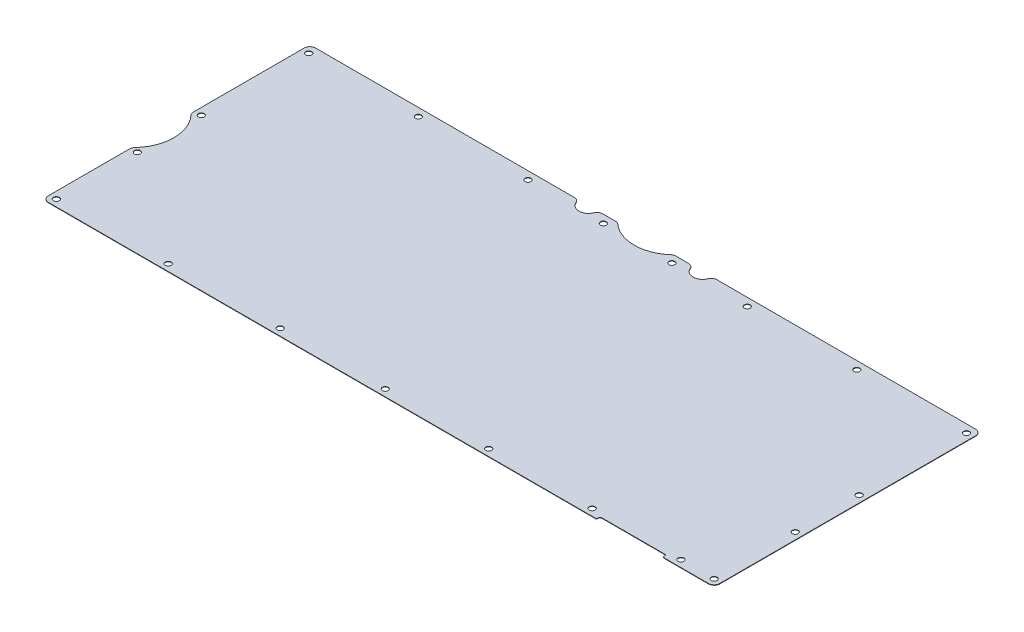
SolidWorks part; units mm, degrees
material "PE High Density Film"
ref_plane "Front Plane" through (0, 0, 0) normal (0, 0, 1) x (1, 0, 0)
ref_plane "Top Plane" through (0, 0, 0) normal (0, 1, 0) x (1, 0, 0)
ref_plane "Right Plane" through (0, 0, 0) normal (1, 0, 0) x (0, 0, -1)
sketch "Sketch1" plane through (0, 0, 0) normal (0, 1, 0) x (1, 0, 0)
  line L1 (-186.69, -74.6125) -> (186.69, -74.6125)
  line L2 (-186.69, -74.6125) -> (-186.69, 74.6125)
  line L3 (-186.69, 74.6125) -> (186.69, 74.6125)
  line L4 (186.69, -74.6125) -> (186.69, 74.6125)
  line L5 (-186.69, -74.6125) -> (186.69, 74.6125) construction
  line L6 (-186.69, 74.6125) -> (186.69, -74.6125) construction
  point P0 (0, 0)
  dimension "D1" = 149.225
  dimension "D2" = 373.38
extrude "Boss-Extrude1" add sketch "Sketch1" along normal blind 0.254
hole_wizard "#4 Clearance Hole2" positions "Sketch6" profile "Sketch5" hole size "#4" standard "Ansi Inch"
sketch "Sketch6" plane through (0, 0.254, 0) normal (0, 1, 0) x (-1, 0, 0)
  line L0 (-186.69, -74.6125) -> (186.69, -74.6125) construction
  line L1 (186.69, -74.6125) -> (186.69, 74.6125) construction
  point P0 (121.92, -70.1675)
  point P15 (60.96, -70.1675)
  point P16 (0, -70.1675)
  point P17 (-60.96, -70.1675)
  point P18 (-121.92, -70.1675)
  dimension "D1" = 4.445
  dimension "D2" = 64.77
  dimension "D4" = 60.96
  dimension "D3" = 5
sketch "Sketch5" plane through (-121.92, 0.254, -70.1675) normal (1, 0, 0) x (0, 0, 1)
  line L0 (0, 0) -> (0, 1.7426)
  line L1 (0, 1.7426) -> (1.6319, 0.762)
  line L2 (1.6319, 0.762) -> (1.6319, 0)
  line L5 (1.6319, 0) -> (0, 0)
  line L10 (0, 1.7426) -> (-1.6319, 0.762) construction
  line L11 (0, -6.35) -> (0, 107.95) construction
  dimension "Hole Dia." = 3.2639
  dimension "Hole Depth" = 0.762
  dimension "Drill Angle" = 118
sketch "Sketch7" plane through (0, 0.254, 0) normal (0, 1, 0) x (1, 0, 0)
  line L0 (186.69, 74.6125) -> (-186.69, 74.6125) construction
  circle A0 centre (0, 90.4875) radius 22.225
  dimension "D2" = 44.45
  dimension "D1" = 15.875
extrude "Cut-Extrude2" cut sketch "Sketch7" against normal up to next
fillet "Fillet2" radius 3.175 2 edges at (15.5543, 0.127, -74.6125) (-15.5543, 0.127, -74.6125)
hole_wizard "#4 Clearance Hole3" positions "Sketch9" profile "Sketch8" hole size "#4" standard "Ansi Inch" end condition up to next
sketch "Sketch9" plane through (0, 0.254, 0) normal (0, 1, 0) x (-1, 0, 0)
  line L0 (-186.69, -74.6125) -> (-16.8005, -74.6125) construction
  point P0 (19.05, -70.1675)
  point P1 (-19.05, -70.1675)
  dimension "D1" = 4.445
  dimension "D2" = 19.05
  dimension "D3" = 38.1
sketch "Sketch8" plane through (-19.05, 0.254, -70.1675) normal (1, 0, 0) x (0, 0, 1)
  line L0 (0, 0) -> (0, 0.254)
  line L1 (0, 0.254) -> (1.632, 0.254)
  line L2 (1.632, 0.254) -> (1.6319, 0)
  line L5 (1.6319, 0) -> (0, 0)
  line L11 (0, -6.35) -> (0, 107.95) construction
  dimension "Thru Hole Dia." = 3.2639
  dimension "Thru Hole Depth" = 0.254
sketch "Sketch10" plane through (0, 0.254, 0) normal (0, 1, 0) x (1, 0, 0)
  line L0 (186.69, 74.6125) -> (16.8005, 74.6125) construction
  circle A0 centre (31.75, 74.6125) radius 5.334
  circle A1 centre (-31.75, 74.6125) radius 5.334
  dimension "D1" = 10.668
  dimension "D2" = 63.5
  dimension "D3" = 31.75
extrude "Cut-Extrude3" cut sketch "Sketch10" against normal blind 1.016
fillet "Fillet3" radius 3.175 4 edges at (-37.084, 0.127, -74.6125) (-26.416, 0.127, -74.6125) (26.416, 0.127, -74.6125) (37.084, 0.127, -74.6125)
sketch "Sketch11" plane through (0, 0.254, 0) normal (0, 1, 0) x (1, 0, 0)
  line L0 (-186.69, 74.6125) -> (-186.69, -74.6125) construction
  line L1 (-39.6445, 74.6125) -> (-186.69, 74.6125) construction
  circle A0 centre (-202.565, -7.9375) radius 22.86
  dimension "D2" = 45.72
  dimension "D1" = 15.875
  dimension "D3" = 82.55
extrude "Cut-Extrude4" cut sketch "Sketch11" against normal through all
fillet "Fillet4" radius 3.175 4 edges at (186.69, 0.127, -74.6125) (-186.69, 0.127, -74.6125) (-186.69, 0.127, 24.3863) (-186.69, 0.127, -8.5113)
hole_wizard "#4 Clearance Hole4" positions "Sketch13" profile "Sketch14" hole size "#4" standard "Ansi Inch" end condition up to next
sketch "Sketch13" plane through (0, 0.254, 0) normal (0, 1, 0) x (-1, 0, 0)
  line L0 (186.69, 74.6125) -> (-186.69, 74.6125) construction
  line L1 (186.69, 25.6834) -> (186.69, 74.6125) construction
  line L2 (39.6445, -74.6125) -> (183.515, -74.6125) construction
  point P1 (182.88, -70.1675)
  point P3 (182.88, -10.4775)
  point P5 (182.88, 25.0825)
  point P7 (182.88, 70.1675)
  dimension "D1" = 4.445
  dimension "D2" = 3.81
  dimension "D3" = 45.085
  dimension "D4" = 4.445
  dimension "D5" = 35.56
sketch "Sketch14" plane through (-182.88, 0.254, -70.1675) normal (1, 0, 0) x (0, 0, 1)
  line L0 (0, 0) -> (0, 0.255)
  line L1 (0, 0.255) -> (1.632, 0.255)
  line L2 (1.632, 0.255) -> (1.6319, 0)
  line L5 (1.6319, 0) -> (0, 0)
  line L11 (0, -6.35) -> (0, 107.95) construction
  dimension "Thru Hole Dia." = 3.2639
  dimension "Thru Hole Depth" = 0.255
mirror "Mirror1" about plane through (0, 0, 0) normal (1, 0, 0) of "#4 Clearance Hole4"
sketch "Sketch15" plane through (0, 0.254, 0) normal (0, 1, 0) x (1, 0, 0)
  line L0 (-186.69, -74.6125) -> (186.69, -74.6125) construction
  line L1 (158.0515, -74.6125) -> (121.3485, -74.6125)
  line L2 (158.0515, -74.6125) -> (158.0515, -72.009)
  line L3 (158.0515, -72.009) -> (121.3485, -72.009)
  line L4 (121.3485, -74.6125) -> (121.3485, -72.009)
  line L5 (186.69, -74.6125) -> (186.69, 71.4375) construction
  dimension "D1" = 2.6035
  dimension "D2" = 36.703
  dimension "D3" = 28.6385
extrude "Cut-Extrude5" cut sketch "Sketch15" against normal through all
hole_wizard "#4 Clearance Hole5" positions "Sketch17" profile "Sketch18" hole size "#4" standard "Ansi Inch" end condition up to next
sketch "Sketch17" plane through (0, 0.254, 0) normal (0, 1, 0) x (-1, 0, 0)
  line L1 (-186.69, 74.6125) -> (-186.69, -71.4375) construction
  line L3 (-158.0515, 74.6125) -> (-186.69, 74.6125) construction
  circle A0 centre (182.88, 70.1675) radius 1.6319 construction
  point P0 (-115.062, 70.1675)
  point P1 (-164.465, 70.1675)
  point P9 (0, 70.1675)
  point P11 (-57.531, 70.1675)
  point P13 (120.65, 70.1675)
  point P15 (58.42, 70.1675)
  dimension "D5" = 62.23
  dimension "D1" = 4.445
  dimension "D2" = 49.403
  dimension "D3" = 22.225
  dimension "D4" = 57.531
  dimension "D6" = 62.23
sketch "Sketch18" plane through (115.062, 0.254, 70.1675) normal (1, 0, 0) x (0, 0, 1)
  line L0 (0, 0) -> (0, 0.254)
  line L1 (0, 0.254) -> (1.632, 0.254)
  line L2 (1.632, 0.254) -> (1.6319, 0)
  line L5 (1.6319, 0) -> (0, 0)
  line L11 (0, -6.35) -> (0, 107.95) construction
  dimension "Thru Hole Dia." = 3.2639
  dimension "Thru Hole Depth" = 0.254
sketch "Sketch20" plane through (0, 0.254, 0) normal (0, 1, 0) x (1, 0, 0)
  line L0 (186.69, -74.6125) -> (186.69, 71.4375) construction
  line L1 (-186.69, -74.6125) -> (186.69, -74.6125)
  line L2 (-186.69, -74.6125) -> (-186.69, -73.9775)
  line L3 (-186.69, -73.9775) -> (186.69, -73.9775)
  line L4 (186.69, -74.6125) -> (186.69, -73.9775)
  dimension "D1" = 0.635
extrude "Cut-Extrude6" cut sketch "Sketch20" against normal through all
fillet "Fillet6" radius 0.762 4 edges at (121.3485, 0.127, 72.009) (121.3485, 0.127, 73.9775) (158.0515, 0.127, 73.9775) (158.0515, 0.127, 72.009)
fillet "Fillet7" radius 3.175 2 edges at (-186.69, 0.127, 73.9775) (186.69, 0.127, 73.9775)
